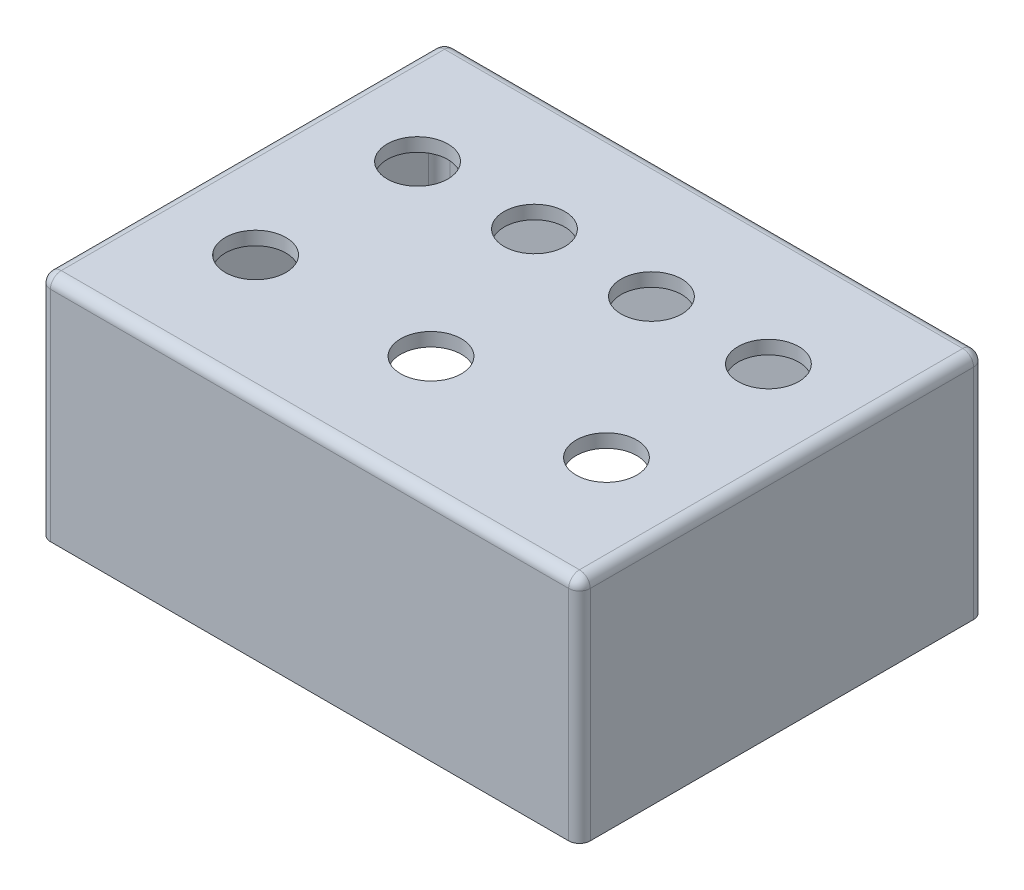
SolidWorks part; units mm, degrees
ref_plane "Plano frontal" through (0, 0, 0) normal (0, 0, 1) x (1, 0, 0)
ref_plane "Plano superior" through (0, 0, 0) normal (0, 1, 0) x (1, 0, 0)
ref_plane "Plano direito" through (0, 0, 0) normal (1, 0, 0) x (0, 0, -1)
sketch "Esboço1" plane through (0, 0, 0) normal (0, 1, 0) x (1, 0, 0)
  line L1 (100, -75) -> (-100, -75)
  line L2 (100, -75) -> (100, 75)
  line L3 (100, 75) -> (-100, 75)
  line L4 (-100, -75) -> (-100, 75)
  line L5 (100, -75) -> (-100, 75) construction
  line L6 (100, 75) -> (-100, -75) construction
  point P0 (0, 0)
  dimension "D1" = 200
  dimension "D2" = 150
extrude "Ressalto-extrusão1" add sketch "Esboço1" along normal blind 5
sketch "Esboço2" plane through (0, 0, 0) normal (0, -1, 0) x (1, 0, 0)
  line L0 (100, -75) -> (-100, -75) construction
  line L1 (-100, 75) -> (-97, 75)
  line L2 (-100, 75) -> (-100, -75)
  line L3 (-100, -75) -> (-97, -75)
  line L4 (-97, 75) -> (-97, -75)
  line L6 (100, 75) -> (97, 75)
  line L7 (100, 75) -> (100, -75)
  line L8 (100, -75) -> (97, -75)
  line L9 (97, 75) -> (97, -75)
  dimension "D1" = 3
extrude "Ressalto-extrusão2" add sketch "Esboço2" along normal blind 80
sketch "Esboço3" plane through (0, 5, 0) normal (0, 1, 0) x (1, 0, 0)
  line L0 (-100, 30) -> (-65, 30) construction
  line L1 (100, 75) -> (-100, 75) construction
  line L2 (-100, -75) -> (100, -75) construction
  line L3 (-100, 75) -> (-100, -75) construction
  line L4 (-65, 30) -> (-21.6667, 30) construction
  line L5 (-21.6667, 30) -> (21.6667, 30) construction
  line L6 (21.6667, 30) -> (65, 30) construction
  line L7 (65, 30) -> (100, 30) construction
  line L10 (100, -75) -> (100, 75) construction
  line L11 (-100, -30) -> (-65, -30) construction
  line L13 (-65, -30) -> (0, -30) construction
  line L16 (0, -30) -> (65, -30) construction
  line L17 (65, -30) -> (100, -30) construction
  circle A0 centre (-65, 30) radius 11.25
  circle A1 centre (-21.6667, 30) radius 11.25
  circle A2 centre (21.6667, 30) radius 11.25
  circle A3 centre (65, 30) radius 11.25
  circle A4 centre (-65, -30) radius 11.25
  circle A5 centre (0, -30) radius 11.25
  circle A6 centre (65, -30) radius 11.25
  point P26 (0, 0)
  point P27 (0, 0)
  point P28 (65, 40)
  dimension "D1" = 35
  dimension "D3" = 22.5
  dimension "D2" = 45
  dimension "D4" = 45
  dimension "D5" = 35
extrude "Corte-extrusão1" cut sketch "Esboço3" against normal up to surface (5 mm away) up to face at (0, 0, 0)
sketch "Esboço6" plane through (0, 0, 0) normal (0, -1, 0) x (1, 0, 0)
  line L0 (-97, -75) -> (-97, 75) construction
  line L1 (-97, -70) -> (97, -70)
  line L2 (-97, -70) -> (-97, -75)
  line L3 (-97, -75) -> (97, -75)
  line L4 (97, -70) -> (97, -75)
  line L5 (97, 75) -> (97, -75) construction
  line L6 (-97, 75) -> (97, 75)
  line L7 (-97, 75) -> (-97, 70)
  line L8 (-97, 70) -> (97, 70)
  line L9 (97, 75) -> (97, 70)
  dimension "D1" = 5
  dimension "D2" = 5
extrude "Ressalto-extrusão3" add sketch "Esboço6" along normal blind 80
fillet "Filete2" radius 4 8 edges at (100, -37.5, -75) (100, -37.5, 75) (100, 5, 0) (0, 5, 75) (-100, -37.5, 75) (-100, 5, 0) (0, 5, -75) (-100, -37.5, -75)
fillet "Filete3" radius 4 8 edges at (-97, -40, -70) (97, -40, 70) (97, -40, -70) (0, 0, -70) (97, 0, 0) (0, 0, 70) (-97, 0, 0) (-97, -40, 70)
sketch "Esboço10" plane through (0, 0, 75) normal (0, 0, 1) x (1, 0, 0)
sketch "Esboço12" plane through (0, 0, -75) normal (0, 0, -1) x (-1, 0, 0)
  circle A0 centre (0, -55.4447) radius 14.2293
  point P2 (0, -55.4447)
  point P3 (0, 0)
extrude "Corte-extrusão3" cut sketch "Esboço12" against normal up to surface (5 mm away) contours A0 up to face at (0, -42, -70)
